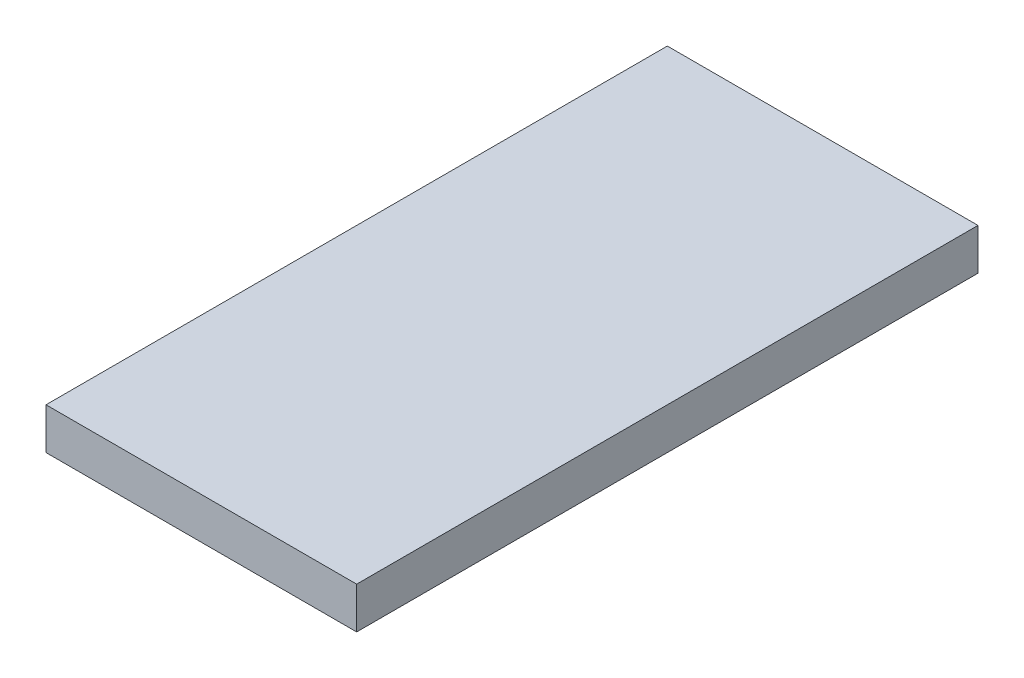
SolidWorks part; units mm, degrees
ref_plane "Front Plane" through (0, 0, 0) normal (0, 0, 1) x (1, 0, 0)
ref_plane "Top Plane" through (0, 0, 0) normal (0, 1, 0) x (1, 0, 0)
ref_plane "Right Plane" through (0, 0, 0) normal (1, 0, 0) x (0, 0, -1)
sketch "Sketch1" plane through (0, 0, 0) normal (0, 0, 1) x (1, 0, 0)
  line L0 (0, 0) -> (60, 0)
  line L1 (60, 0) -> (60, 8)
  line L2 (60, 8) -> (0, 8)
  line L6 (0, 8) -> (0, 0)
  dimension "D1" = 60
  dimension "D2" = 8
extrude "Boss-Extrude1" add sketch "Sketch1" along normal blind 120
sketch "Sketch2" plane through (0, 0, 0) normal (0, -1, 0) x (-1, 0, 0)
  line L0 (-17.1014, 0) -> (-17.1014, -120) construction
  line L1 (0, 0) -> (-60, 0) construction
  line L2 (0, -120) -> (-60, -120) construction
  point P9 (-17.1014, -60)
  point P20 (-17.1014, -40)
  point P21 (-17.1014, -20)
  point P22 (-17.1014, -60)
  point P23 (-17.1014, -40)
  point P24 (-17.1014, -80)
  point P25 (-17.1014, -60)
  point P26 (-17.1014, -80)
  point P27 (-17.1014, -100)
  dimension "D1" = 3
  dimension "D2" = 3
hole_wizard "CBORE for M3 Hex Socket Head Cap Screw1" positions "Sketch2" profile "Sketch4" counterbore size "M3" standard "DIN"
sketch "Sketch4" plane through (17.1014, 0, 100) normal (1, 0, 0) x (0, 0, -1)
  line L0 (0, 0) -> (0, 7.0215)
  line L1 (0, 7.0215) -> (1.7, 6)
  line L2 (1.7, 6) -> (1.7, 3.4)
  line L3 (1.7, 3.4) -> (3.25, 3.4)
  line L5 (3.25, 3.4) -> (3.25, 0.025)
  line L6 (3.25, 0.025) -> (3.275, 0)
  line L7 (3.275, 0) -> (0, 0)
  line L8 (-3.25, 0.025) -> (-3.275, 0) construction
  line L10 (0, 7.0215) -> (-1.7, 6) construction
  line L11 (0, -6.35) -> (0, 107.95) construction
  dimension "Hole Dia." = 3.4
  dimension "Hole Depth" = 6
  dimension "C'Bore Dia." = 6.5
  dimension "C'Bore Depth" = 3.4
  dimension "Near C'Sink Dia." = 6.55
  dimension "Near C'Sink Angle" = 90
  dimension "Drill Angle" = 118
